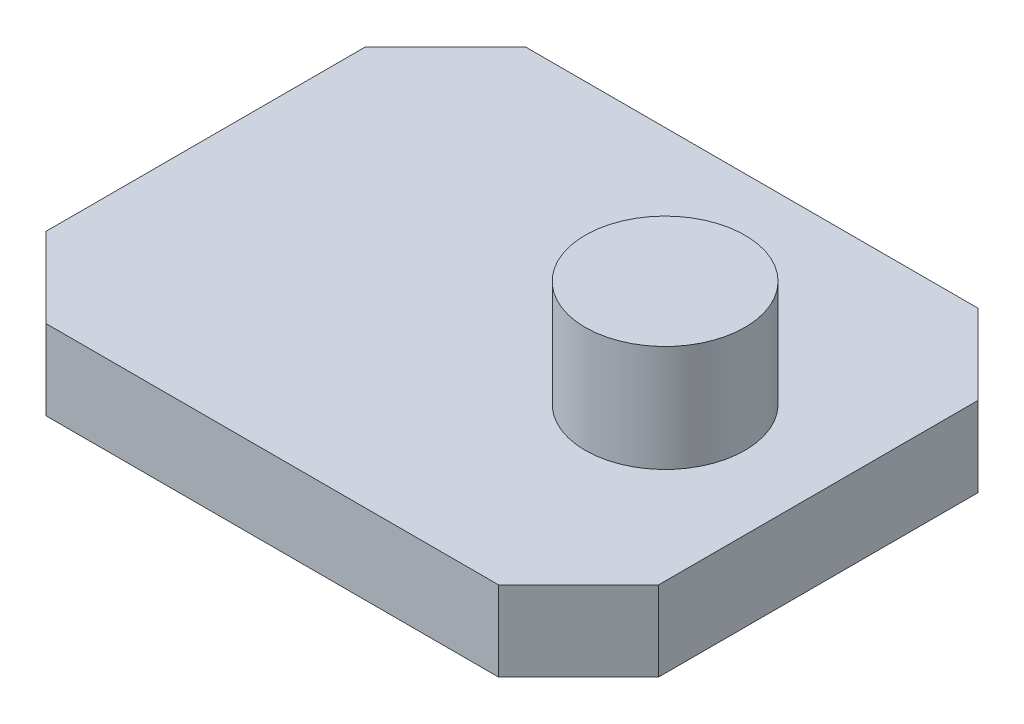
SolidWorks part; units mm, degrees
material "Plain Carbon Steel"
ref_plane "Front Plane" through (0, 0, 0) normal (0, 0, 1) x (1, 0, 0)
ref_plane "Top Plane" through (0, 0, 0) normal (0, 1, 0) x (1, 0, 0)
ref_plane "Right Plane" through (0, 0, 0) normal (1, 0, 0) x (0, 0, -1)
sketch "Sketch2" plane through (0, 0, 0) normal (0, 1, 0) x (1, 0, 0)
  line L1 (-11.5, -9) -> (11.5, -9)
  line L2 (-11.5, -9) -> (-11.5, 9)
  line L3 (-11.5, 9) -> (11.5, 9)
  line L4 (11.5, -9) -> (11.5, 9)
  line L5 (-11.5, -9) -> (11.5, 9) construction
  line L6 (-11.5, 9) -> (11.5, -9) construction
  point P0 (0, 0)
  dimension "D1" = 18
  dimension "D2" = 23
extrude "Boss-Extrude1" add sketch "Sketch2" along normal blind 3
sketch "Sketch3" plane through (0, 3, 0) normal (0, 1, 0) x (1, 0, 0)
  line L0 (0, 0) -> (11.5, 0) construction
  line L1 (11.5, -9) -> (11.5, 9) construction
  line L2 (5.75, 0) -> (5.75, -9) construction
  line L3 (-11.5, -9) -> (11.5, -9) construction
  circle A0 centre (5.75, 0) radius 3
  dimension "D1" = 6
extrude "Boss-Extrude2" add sketch "Sketch3" along normal blind 4
chamfer "Chamfer1" distance 3 angle 45 4 edges at (11.5, 1.5, -9) (11.5, 1.5, 9) (-11.5, 1.5, 9) (-11.5, 1.5, -9)
